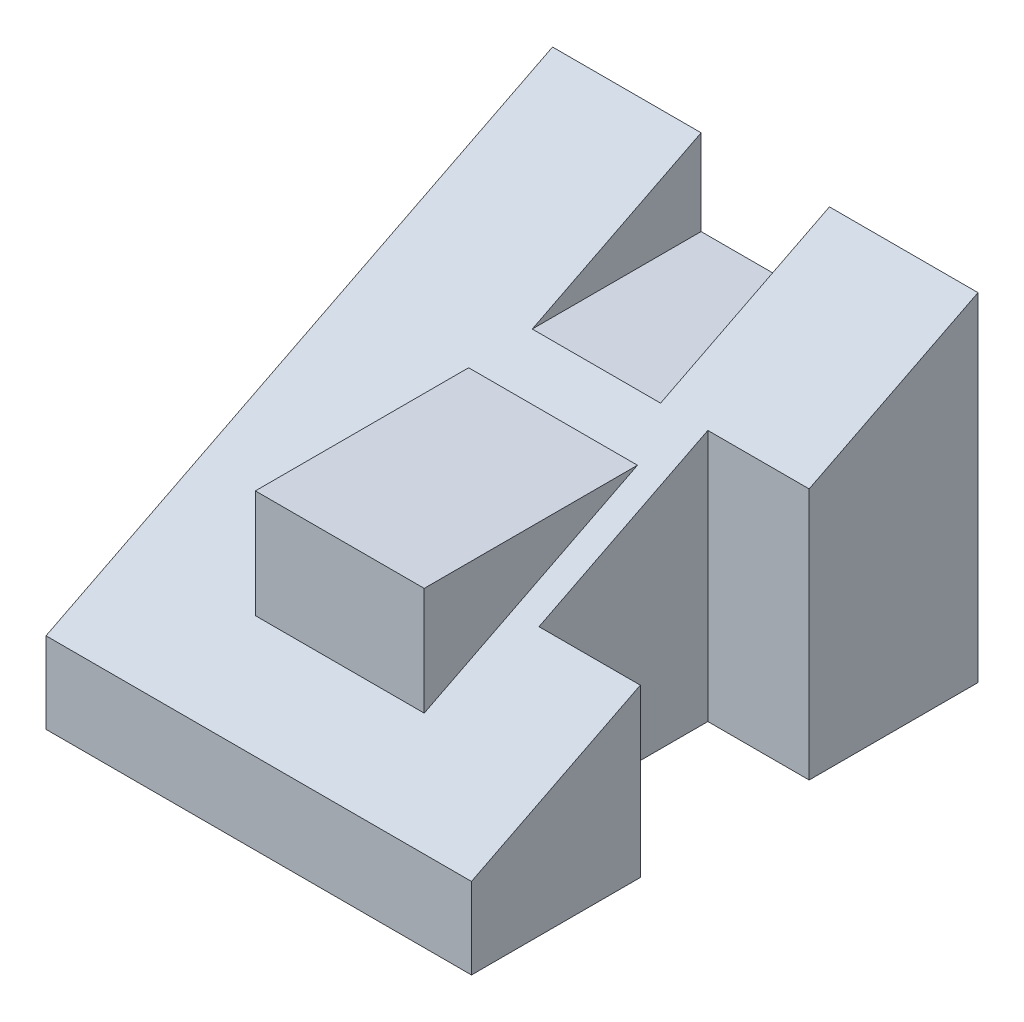
SolidWorks part; units mm, degrees
ref_plane "Front Plane" through (0, 0, 0) normal (0, 0, 1) x (1, 0, 0)
ref_plane "Top Plane" through (0, 0, 0) normal (0, 1, 0) x (1, 0, 0)
ref_plane "Right Plane" through (0, 0, 0) normal (1, 0, 0) x (0, 0, -1)
sketch "Sketch1" plane through (0, 0, 0) normal (1, 0, 0) x (0, 0, -1)
  line L0 (75, 0) -> (75, 50)
  line L1 (75, 50) -> (0, 12)
  line L2 (0, 12) -> (0, 0)
  line L3 (0, 0) -> (75, 0)
  dimension "D1" = 75
  dimension "D2" = 50
  dimension "D3" = 12
extrude "Boss-Extrude1" add sketch "Sketch1" against normal blind 63
sketch "Sketch2" plane through (0, 0, 0) normal (1, 0, 0) x (0, 0, -1)
  line L0 (50, 0) -> (50, 37.3333)
  line L1 (0, 0) -> (75, 0) construction
  line L2 (75, 50) -> (0, 12) construction
  line L3 (50, 37.3333) -> (25, 24.6667)
  line L4 (25, 24.6667) -> (25, 0)
  line L5 (25, 0) -> (50, 0)
  dimension "D1" = 25
  dimension "D2" = 25
extrude "Cut-Extrude1" cut sketch "Sketch2" against normal blind 15 contours L5 L0 L3 L4
ref_plane "Plane1" through (-19, 0, 0) normal (1, 0, 0) x (0, 0, -1)
sketch "Sketch4" plane through (-19, 0, 0) normal (1, 0, 0) x (0, 0, -1)
  line L0 (12, 18.08) -> (12, 34.08)
  line L1 (25, 24.6667) -> (0, 12) construction
  line L2 (12, 34.08) -> (43.5789, 34.08)
  line L3 (50, 37.3333) -> (25, 24.6667) construction
  line L4 (12, 18.08) -> (43.5789, 34.08)
  dimension "D1" = 12
  dimension "D2" = 16
extrude "Boss-Extrude2" add sketch "Sketch4" against normal blind 25
ref_plane "Plane2" through (-22, 0, 0) normal (1, 0, 0) x (0, 0, -1)
sketch "Sketch5" plane through (-22, 0, 0) normal (1, 0, 0) x (0, 0, -1)
  line L0 (75, 50) -> (50, 37.3333)
  line L1 (50, 37.3333) -> (75, 37.3333)
  line L2 (75, 0) -> (75, 50) construction
  line L3 (75, 50) -> (75, 37.3333)
extrude "Cut-Extrude2" cut sketch "Sketch5" against normal blind 19
